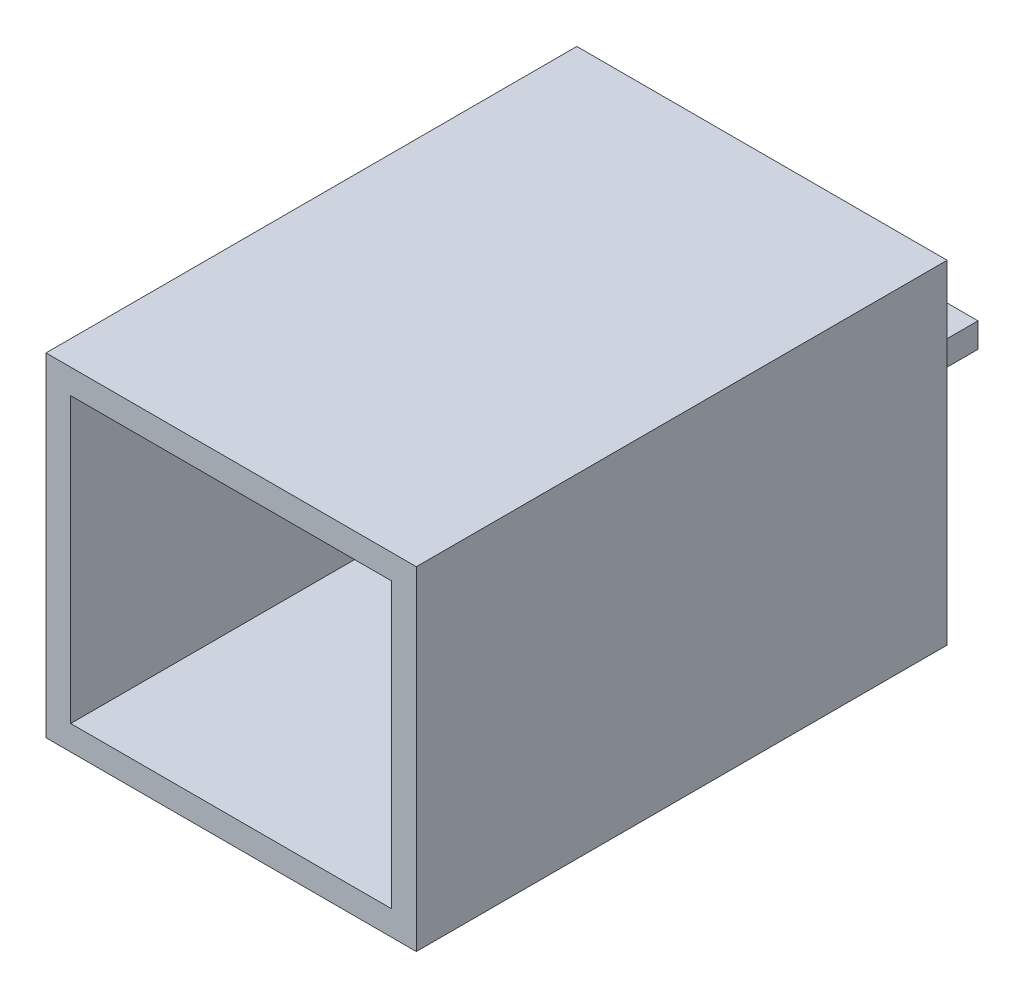
SolidWorks part; units mm, degrees
ref_plane "Front Plane" through (0, 0, 0) normal (0, 0, 1) x (1, 0, 0)
ref_plane "Top Plane" through (0, 0, 0) normal (0, 1, 0) x (1, 0, 0)
ref_plane "Right Plane" through (0, 0, 0) normal (1, 0, 0) x (0, 0, -1)
sketch "Sketch1" plane through (0, 0, 0) normal (0, 0, 1) x (1, 0, 0)
  line L1 (-13, 11.5) -> (13, 11.5)
  line L2 (-13, 11.5) -> (-13, -11.5)
  line L3 (-13, -11.5) -> (13, -11.5)
  line L4 (13, 11.5) -> (13, -11.5)
  line L5 (-13, 11.5) -> (13, -11.5) construction
  line L6 (-13, -11.5) -> (13, 11.5) construction
  line L7 (-15, 13.5) -> (15, 13.5)
  line L8 (-15, 13.5) -> (-15, -13.5)
  line L9 (-15, -13.5) -> (15, -13.5)
  line L10 (15, 13.5) -> (15, -13.5)
  line L11 (-15, 13.5) -> (15, -13.5) construction
  line L12 (-15, -13.5) -> (15, 13.5) construction
  point P0 (0, 0)
  point P6 (0, 0)
  dimension "D1" = 23
  dimension "D2" = 26
  dimension "D3" = 2
  dimension "D4" = 2
extrude "Boss-Extrude1" add sketch "Sketch1" along normal blind 43
sketch "Sketch3" plane through (0, 0, 0) normal (0, 0, -1) x (-1, 0, 0)
  line L0 (15, 13.5) -> (15, -13.5) construction
  line L1 (-15, 13.5) -> (15, 13.5)
  line L2 (-15, 13.5) -> (-15, -1.5)
  line L3 (-15, -1.5) -> (15, -1.5)
  line L4 (15, 13.5) -> (15, -1.5)
  line L5 (13, -11.5) -> (-13, -11.5) construction
  dimension "D1" = 10
extrude "Boss-Extrude2" add sketch "Sketch3" against normal blind 2
sketch "Sketch5" plane through (0, 0, 0) normal (0, 0, -1) x (-1, 0, 0)
  line L0 (-13, -1.5) -> (13, -1.5) construction
  line L1 (-7.5, -1.5) -> (7.5, -1.5)
  line L2 (-7.5, -1.5) -> (-7.5, 0.5)
  line L3 (-7.5, 0.5) -> (7.5, 0.5)
  line L4 (7.5, -1.5) -> (7.5, 0.5)
  line L5 (0, 0) -> (0, -1.5) construction
  line L6 (13, -11.5) -> (-13, -11.5) construction
  line L7 (-2.5, -11.5) -> (2.5, -11.5)
  line L8 (-2.5, -11.5) -> (-2.5, -13.5)
  line L9 (-2.5, -13.5) -> (2.5, -13.5)
  line L10 (2.5, -11.5) -> (2.5, -13.5)
  line L11 (15, -13.5) -> (-15, -13.5) construction
  point P17 (0, -11.5)
  dimension "D1" = 15
  dimension "D2" = 2
  dimension "D3" = 5
extrude "Boss-Extrude3" add sketch "Sketch5" along normal blind 10 contours L2 L1 L4 L3 | L8 L7 L10 L9
sketch "Sketch6" plane through (-2.5, 0, 0) normal (-1, 0, 0) x (0, 0, 1)
  line L0 (-5, -13.5) -> (-3, -15.5)
  line L1 (-10, -13.5) -> (0, -13.5) construction
  line L2 (-3, -15.5) -> (-3, -13.5)
  line L3 (-5, -13.5) -> (-3, -13.5)
  line L4 (0, -11.5) -> (0, -13.5) construction
  dimension "D1" = 2
  dimension "D2" = 3
  dimension "D3" = 2
extrude "Boss-Extrude4" add sketch "Sketch6" against normal blind 5
sketch "Sketch7" plane through (0, 0, -10) normal (0, 0, -1) x (-1, 0, 0)
  line L0 (2.5, -11.5) -> (2.5, -13.5) construction
  line L1 (-2.5, -11.5) -> (2.5, -11.5)
  line L2 (-2.5, -11.5) -> (-2.5, -13.5)
  line L3 (-2.5, -13.5) -> (2.5, -13.5)
  line L4 (2.5, -11.5) -> (2.5, -13.5)
  line L5 (2.5, -11.5) -> (2.5, -13.5) construction
extrude "Cut-Extrude1" cut sketch "Sketch7" against normal blind 5
fillet "Fillet3" radius 0.5 3 edges at (0, -11.5, -5) (0, -13.5, -5) (0, -15.5, -3)
